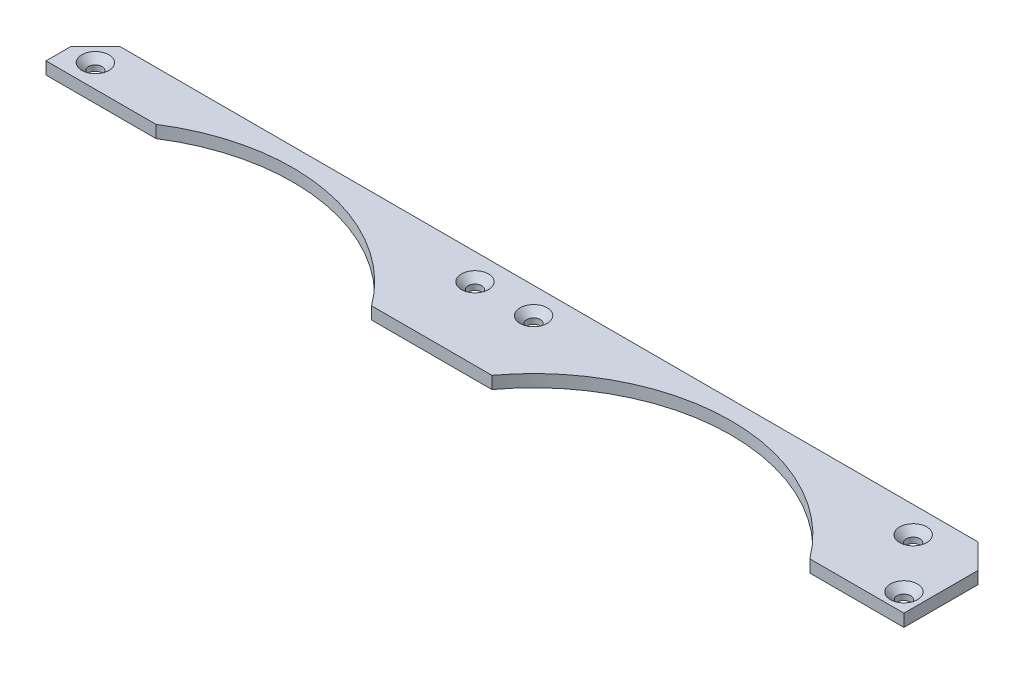
SolidWorks part; units mm, degrees
ref_plane "前视基准面" through (0, 0, 0) normal (0, 0, 1) x (1, 0, 0)
ref_plane "上视基准面" through (0, 0, 0) normal (0, 1, 0) x (1, 0, 0)
ref_plane "右视基准面" through (0, 0, 0) normal (1, 0, 0) x (0, 0, -1)
sketch "草图1" plane through (0, 0, 0) normal (0, 1, 0) x (1, 0, 0)
  line L1 (0, -37) -> (147, -37)
  line L2 (0, -37) -> (0, 0)
  line L3 (0, 0) -> (147, 0)
  line L4 (147, -37) -> (147, 0)
  dimension "D1" = 37
  dimension "D2" = 147
extrude "凸台-拉伸1" add sketch "草图1" along normal blind 2
sketch "草图2" plane through (0, 2, 0) normal (0, 1, 0) x (1, 0, 0)
  line L1 (147, 0) -> (0, 0) construction
  line L2 (147, -37) -> (147, 0) construction
  circle A1 centre (144, -13) radius 1
  dimension "D3" = 3
  dimension "D4" = 13
extrude "螺孔" cut sketch "草图2" against normal blind 2
sketch "草图5" plane through (0, 2, 0) normal (0, 1, 0) x (1, 0, 0)
  line L0 (147, 0) -> (0, 0) construction
  line L1 (141, 0) -> (71, 0) construction
  line L2 (141, 0) -> (141, -70) construction
  line L3 (141, -70) -> (71, -70) construction
  line L4 (71, 0) -> (71, -70) construction
  line L5 (147, -37) -> (147, 0) construction
  line L7 (75.25, -65.75) -> (136.75, -65.75) construction
  line L8 (75.25, -65.75) -> (75.25, -4.25) construction
  line L9 (75.25, -4.25) -> (136.75, -4.25) construction
  line L10 (136.75, -65.75) -> (136.75, -4.25) construction
  line L11 (0, 0) -> (70, 0) construction
  line L12 (0, 0) -> (0, -70) construction
  line L13 (0, -70) -> (70, -70) construction
  line L14 (70, 0) -> (70, -70) construction
  line L15 (4.25, -65.75) -> (65.75, -65.75) construction
  line L16 (4.25, -65.75) -> (4.25, -4.25) construction
  line L17 (4.25, -4.25) -> (65.75, -4.25) construction
  line L18 (65.75, -65.75) -> (65.75, -4.25) construction
  line L19 (75.25, -4.25) -> (136.75, -65.75) construction
  line L20 (65.75, -4.25) -> (4.25, -65.75) construction
  circle A0 centre (75.25, -4.25) radius 1
  circle A1 centre (136.75, -4.25) radius 1
  circle A2 centre (106, -35) radius 32
  circle A3 centre (4.25, -4.25) radius 1
  circle A4 centre (65.75, -4.25) radius 1
  circle A5 centre (35, -35) radius 32
  dimension "D8" = 6
  dimension "D14" = 70
  dimension "D2" = 70
  dimension "D3" = 70
  dimension "D4" = 4.25
  dimension "D5" = 4.25
  dimension "D6" = 4.25
  dimension "D7" = 4.25
  dimension "D9" = 70
  dimension "D10" = 4.25
  dimension "D11" = 4.25
  dimension "D12" = 4.25
  dimension "D13" = 4.25
  dimension "D15" = 1
extrude "Fans" cut sketch "草图5" against normal blind 10
chamfer "倒角1" distance 4 angle 45 2 edges at (0, 1, 0) (147, 1, 0)
sketch "草图6" plane through (0, 0, 0) normal (0, -1, 0) x (-1, 0, 0)
  line L0 (-143, 0) -> (-4, 0) construction
  line L1 (13.1181, -42.8165) -> (-31.603, -42.8165)
  line L2 (13.1181, -42.8165) -> (13.1181, -8)
  line L3 (13.1181, -8) -> (-31.603, -8)
  line L4 (-31.603, -42.8165) -> (-31.603, -8)
  line L5 (-104.0332, -16) -> (-157.391, -16)
  line L6 (-104.0332, -16) -> (-104.0332, -50.8165)
  line L7 (-104.0332, -50.8165) -> (-157.391, -50.8165)
  line L8 (-157.391, -16) -> (-157.391, -50.8165)
  line L10 (-60.1201, -39.8828) -> (-85.4663, -39.8828)
  line L11 (-60.1201, -39.8828) -> (-60.1201, -16)
  line L12 (-60.1201, -16) -> (-85.4663, -16)
  line L13 (-85.4663, -39.8828) -> (-85.4663, -16)
  dimension "D1" = 8
  dimension "D2" = 16
  dimension "D3" = 16
extrude "切除-拉伸1" cut sketch "草图6" against normal blind 10
hole_wizard "打孔尺寸(%根据)内六角花形沉头螺钉的类型1" positions "草图7" profile "草图8" countersink size "M6" standard "GB" end condition through all
sketch "草图7" plane through (0, 2, 0) normal (0, 1, 0) x (1, 0, 0)
  point P0 (4.25, -4.25)
  point P3 (65.75, -4.25)
  point P6 (75.25, -4.25)
  point P9 (136.75, -4.25)
  point P12 (144, -13)
sketch "草图8" plane through (4.25, 2, 4.25) normal (1, 0, 0) x (0, 0, 1)
  line L0 (0, 0) -> (0, 2)
  line L1 (0, 2) -> (1.1, 2)
  line L2 (1.1, 2) -> (1.1, 1.1)
  line L3 (1.1, 1.1) -> (2.2, 0)
  line L5 (2.2, 0) -> (0, 0)
  line L6 (-1.1, 1.1) -> (-2.2, 0) construction
  line L11 (0, -6.35) -> (0, 107.95) construction
  dimension "通孔孔直径" = 2.2
  dimension "通孔孔深度" = 2
  dimension "近端锥形沉头孔直径" = 4.4
  dimension "近端锥形沉头孔角度" = 90
